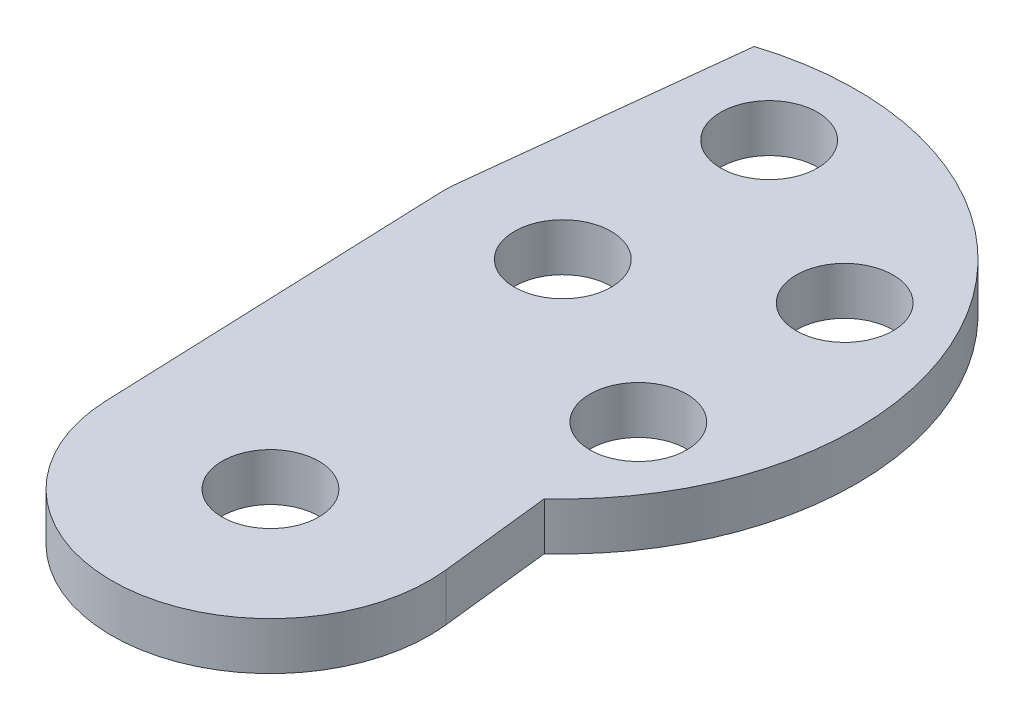
SolidWorks part; units mm, degrees
ref_plane "前视基准面" through (0, 0, 0) normal (0, 0, 1) x (1, 0, 0)
ref_plane "上视基准面" through (0, 0, 0) normal (0, 1, 0) x (1, 0, 0)
ref_plane "右视基准面" through (0, 0, 0) normal (1, 0, 0) x (0, 0, -1)
other "Configuration Table"
sketch "草图1" plane through (0, 0, 0) normal (0, 1, 0) x (1, 0, 0)
  line L0 (11.2583, 6.5) -> (0, 0) construction
  line L1 (11.2583, -6.5) -> (0, 0) construction
  line L2 (0, 0) -> (0, 9.8456) construction
  line L3 (-5.5805, 17.6383) -> (-7.4538, 0.8308)
  line L4 (-3.0074, -6.8706) -> (12.485, -13.652)
  circle A0 centre (0, 0) radius 13 construction
  circle A1 centre (0, 13) radius 3.05
  circle A2 centre (11.2583, -6.5) radius 3.05
  circle A3 centre (11.2583, 6.5) radius 3.05
  circle A4 centre (0, 0) radius 18.5
  circle A5 centre (0, 0) radius 7.5
  dimension "D1" = 26
  dimension "D2" = 6.1
  dimension "D3" = 6.1
  dimension "D5" = 6.1
  dimension "D6" = 37
  dimension "D8" = 15
  dimension "D4" = 60
  dimension "D7" = 60
  dimension "D9" = 53.64
  dimension "D10" = 53.64
extrude "凸台-拉伸1" add sketch "草图1" along normal blind 3 contours A5 | A5 A2 L4 A4 L3 A1 A3
sketch "草图2" plane through (0, 3, 0) normal (0, 1, 0) x (1, 0, 0)
  line L0 (-6.5824, -3.5948) -> (3.3307, -21.7464) construction
  line L1 (-5.5805, 17.6383) -> (-7.4538, 0.8308) construction
  line L2 (-7.4946, -0.2857) -> (-6.6621, -22.1273)
  line L3 (12.485, -13.652) -> (13.2683, -20.631)
  line L4 (-3.0074, -6.8706) -> (12.485, -13.652)
  line L5 (-5.5805, 17.6383) -> (-7.4538, 0.8308)
  line L6 (-3.0074, -6.8706) -> (12.485, -13.652)
  line L7 (-5.5805, 17.6383) -> (-7.4538, 0.8308)
  arc A1 (-7.4538, 0.8308) -> (-3.0074, -6.8706) centre (0, 0) ccw construction
  circle A2 centre (3.3307, -21.7464) radius 10
  circle A3 centre (3.3307, -21.7464) radius 3.05
  arc A4 (-7.4538, 0.8308) -> (-3.0074, -6.8706) centre (0, 0) ccw
  arc A5 (12.485, -13.652) -> (-5.5805, 17.6383) centre (0, 0) ccw
  arc A6 (-7.4538, 0.8308) -> (-3.0074, -6.8706) centre (0, 0) ccw
  arc A7 (12.485, -13.652) -> (-5.5805, 17.6383) centre (0, 0) ccw
  dimension "D4" = 20
  dimension "D5" = 6.1
  dimension "D1" = 145
  dimension "D3" = 22
  dimension "D2" = 0
extrude "凸台-拉伸2" add sketch "草图2" against normal through all
sketch "草图3" plane through (0, 3, 0) normal (0, 1, 0) x (1, 0, 0)
  circle A0 centre (0, 0) radius 3.05
  dimension "D1" = 6.1
extrude "切除-拉伸1" cut sketch "草图3" against normal through all
